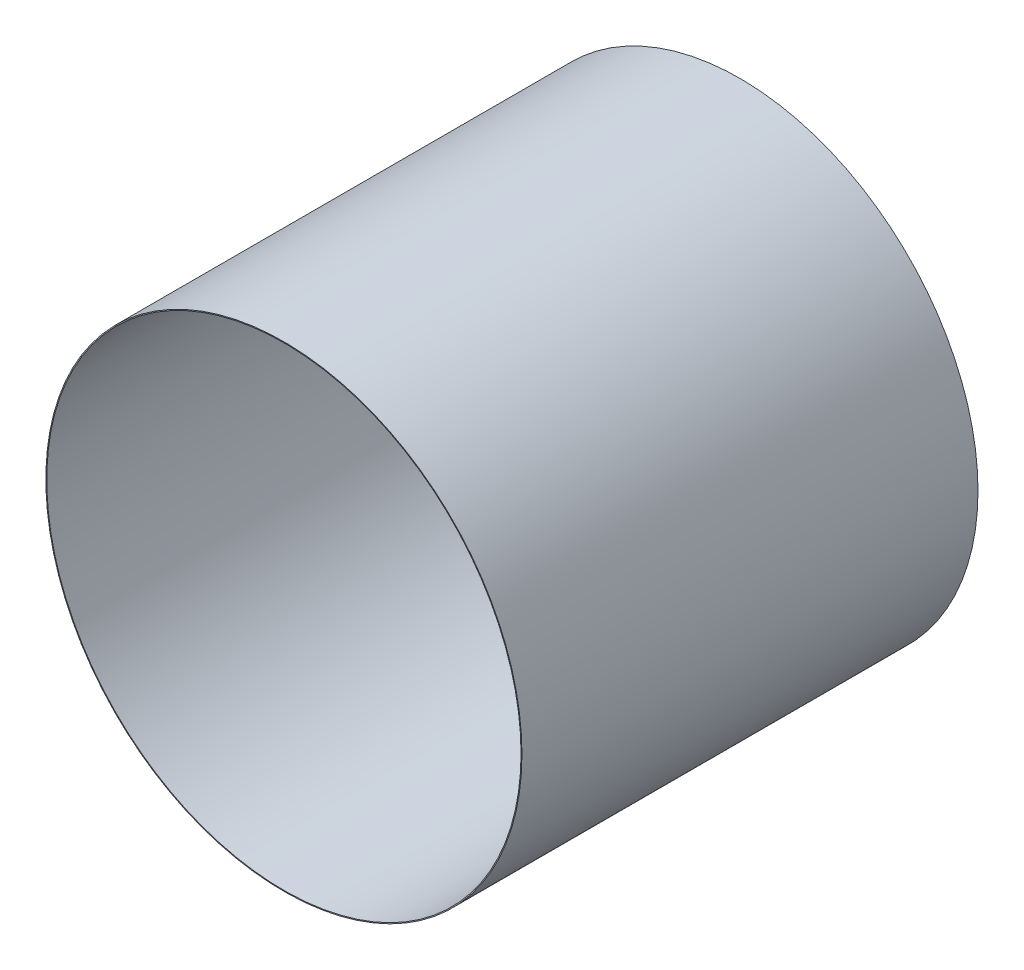
SolidWorks part; units mm, degrees
ref_plane "Front Plane" through (0, 0, 0) normal (0, 0, 1) x (1, 0, 0)
ref_plane "Top Plane" through (0, 0, 0) normal (0, 1, 0) x (1, 0, 0)
ref_plane "Right Plane" through (0, 0, 0) normal (1, 0, 0) x (0, 0, -1)
sketch "Sketch1" plane through (0, 0, 0) normal (0, 0, 1) x (1, 0, 0)
  circle A0 centre (0, 0) radius 13.05
  circle A1 centre (0, 0) radius 13
  dimension "D1" = 26
  dimension "D2" = 26.1
extrude "Boss-Extrude1" add sketch "Sketch1" along normal blind 25
